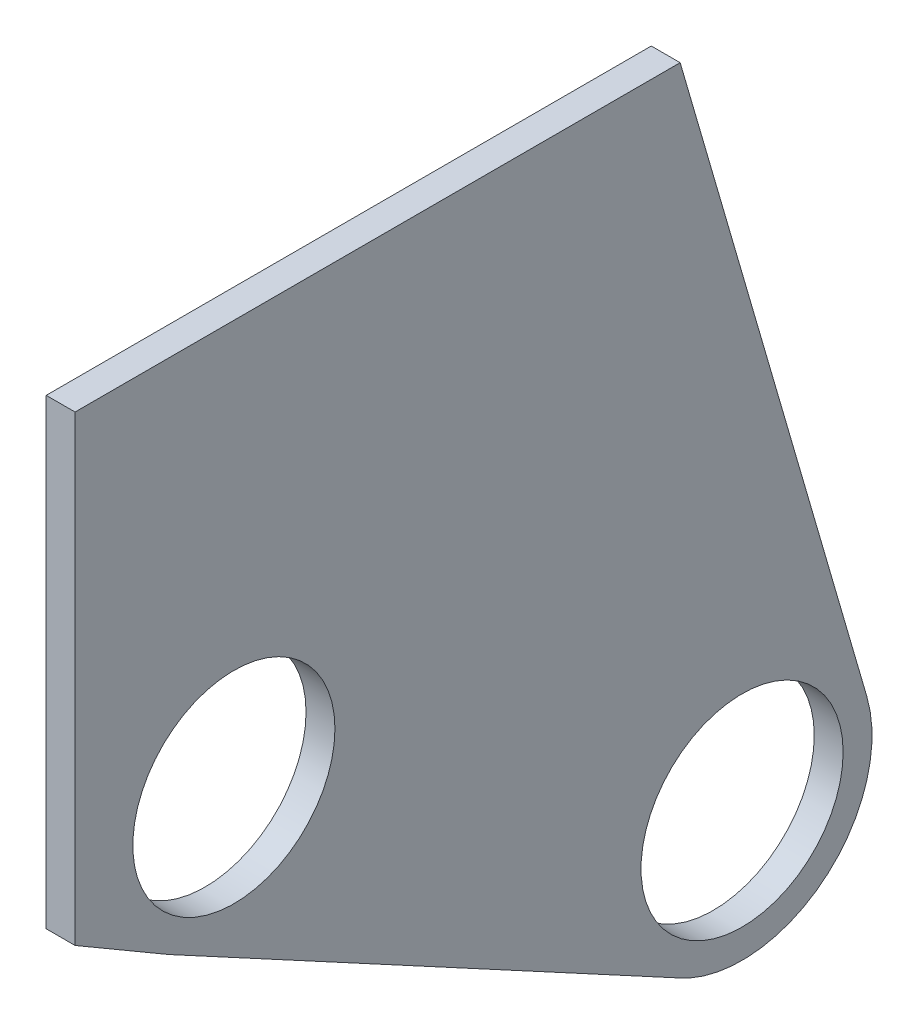
SolidWorks part; units mm, degrees
material "6061-T6 (SS)"
ref_plane "Front" through (0, 0, 0) normal (0, 0, 1) x (1, 0, 0)
ref_plane "Top" through (0, 0, 0) normal (0, 1, 0) x (1, 0, 0)
ref_plane "Right" through (0, 0, 0) normal (1, 0, 0) x (0, 0, -1)
sketch "Sketch2" plane through (0, 0, 0) normal (1, 0, 0) x (0, 0, -1)
  line L4 (63.5, -20.6375) -> (-63.5, -20.6375) construction
  line L5 (-19.0556, 74.6125) -> (12.7962, 74.6125) construction
  line L6 (13.7196, 3.9881) -> (-6.8097, 74.6125)
  line L8 (-7.2029, -12.339) -> (-63.082, 17.8235)
  line L10 (-63.082, 17.8235) -> (-73.3416, 23.8125)
  line L12 (-73.3416, 74.6125) -> (-73.3416, 23.8125)
  line L13 (-6.8097, 74.6125) -> (-73.3416, 74.6125)
  circle A0 centre (-55.8791, 30.1625) radius 11.1125
  circle A1 centre (0, 0) radius 11.1125
  circle A2 centre (-55.8791, 30.1625) radius 12.7 construction
  circle A3 centre (0, 0) radius 12.7 construction
  arc A5 (-7.2029, -12.339) -> (13.7196, 3.9881) centre (0, 0) ccw
  point P17 (0, -20.6375)
  dimension "D1" = 22.225
  dimension "D2" = 25.4
  dimension "D3" = 25.4
  dimension "D4" = 38.1
  dimension "D5" = 3.175
  dimension "D6" = 3.175
  dimension "D7" = 6.35
  dimension "D8" = 38.1
  dimension "D13" = 3.175
  dimension "D14" = 6.35
  dimension "D9" = 50.8
  dimension "D10" = 95.25
  dimension "D11" = 127
  dimension "D12" = 44.45
  dimension "D15" = 63.5
extrude "Boss-Extrude1" add sketch "Sketch2" along normal blind 3.175
